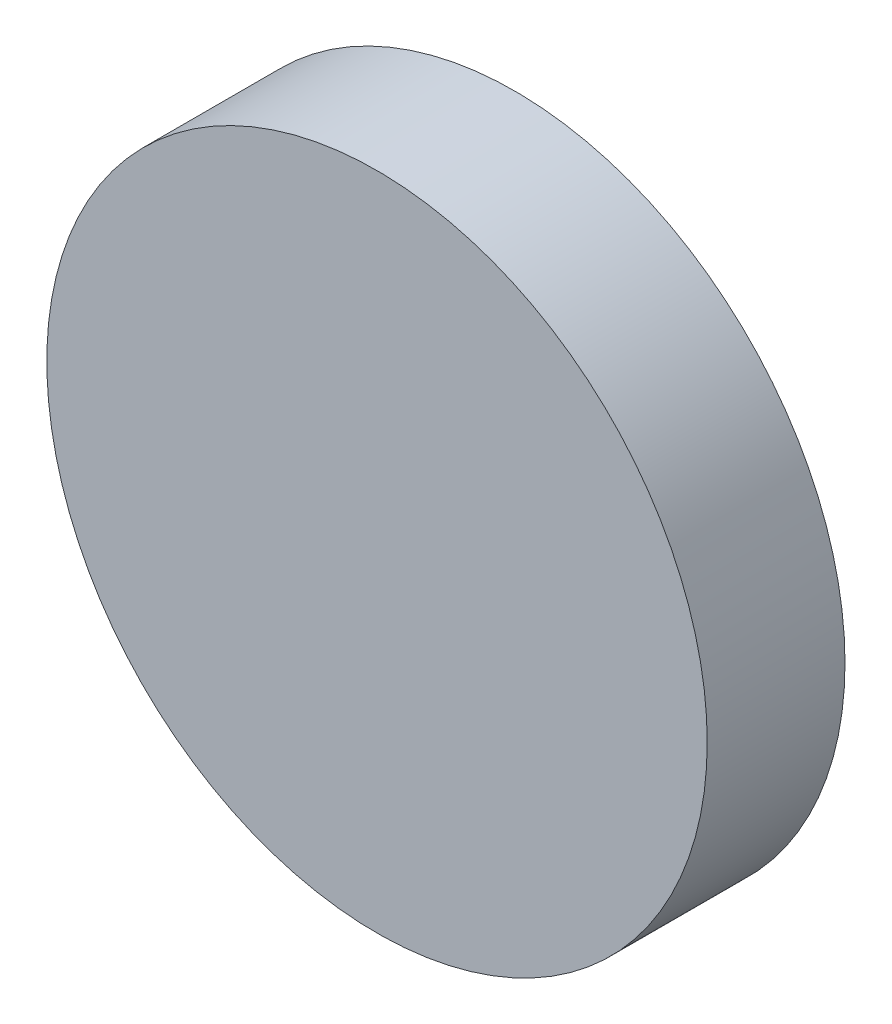
SolidWorks part; units mm, degrees
ref_plane "Plan de face" through (0, 0, 0) normal (0, 0, 1) x (1, 0, 0)
ref_plane "Plan de dessus" through (0, 0, 0) normal (0, 1, 0) x (1, 0, 0)
ref_plane "Plan de droite" through (0, 0, 0) normal (1, 0, 0) x (0, 0, -1)
sketch "Esquisse1" plane through (0, 0, 0) normal (0, 0, 1) x (1, 0, 0)
  circle A0 centre (-63.2639, 46.1363) radius 95.8704
extrude "Boss.-Extru.1" add sketch "Esquisse1" along normal blind 40
